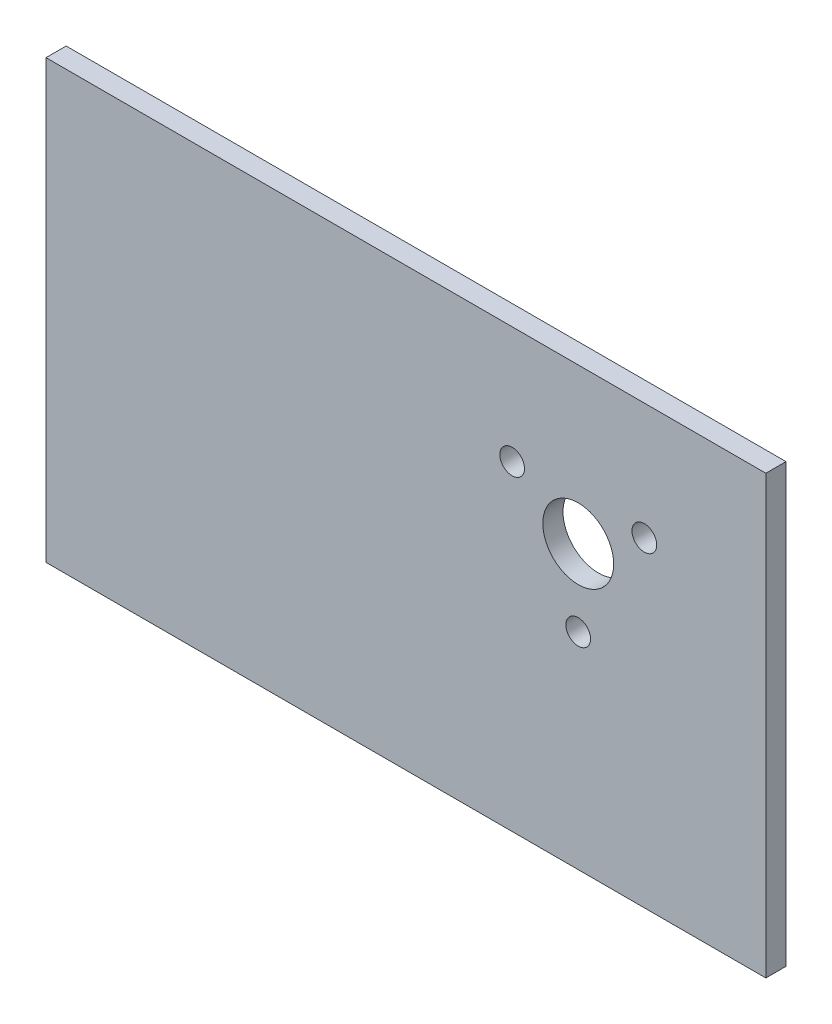
SolidWorks part; units mm, degrees
ref_plane "Front Plane" through (0, 0, 0) normal (0, 0, 1) x (1, 0, 0)
ref_plane "Top Plane" through (0, 0, 0) normal (0, 1, 0) x (1, 0, 0)
ref_plane "Right Plane" through (0, 0, 0) normal (1, 0, 0) x (0, 0, -1)
sketch "Sketch1" plane through (0, 0, 0) normal (0, 0, 1) x (1, 0, 0)
  line L0 (-44.45, -53.848) -> (-50.8, -53.848) construction
  line L1 (98.5006, 83.9325) -> (-128.3795, 83.9325)
  line L2 (98.5006, 83.9325) -> (98.5006, -53.848)
  line L3 (98.5006, -53.848) -> (-128.3795, -53.848)
  line L4 (-128.3795, 83.9325) -> (-128.3795, -53.848)
  circle A0 centre (39.37, 35.1155) radius 11.1633 construction
  circle A1 centre (60.198, 47.1406) radius 6.4326 construction
  circle A2 centre (39.37, 11.0654) radius 6.4325 construction
  circle A3 centre (18.542, 47.1406) radius 6.4325 construction
  circle A4 centre (39.37, 35.1155) radius 11.1633
  circle A5 centre (60.198, 47.1406) radius 6.4326 construction
  circle A6 centre (39.37, 11.0654) radius 6.4325 construction
  circle A7 centre (18.542, 47.1406) radius 6.4325 construction
  circle A8 centre (60.198, 47.1406) radius 3.8925
  circle A9 centre (39.37, 11.0654) radius 3.8925
  circle A10 centre (18.542, 47.1406) radius 3.8925
  dimension "D1" = 2.54
extrude "Boss-Extrude1" add sketch "Sketch1" along normal blind 6.35
